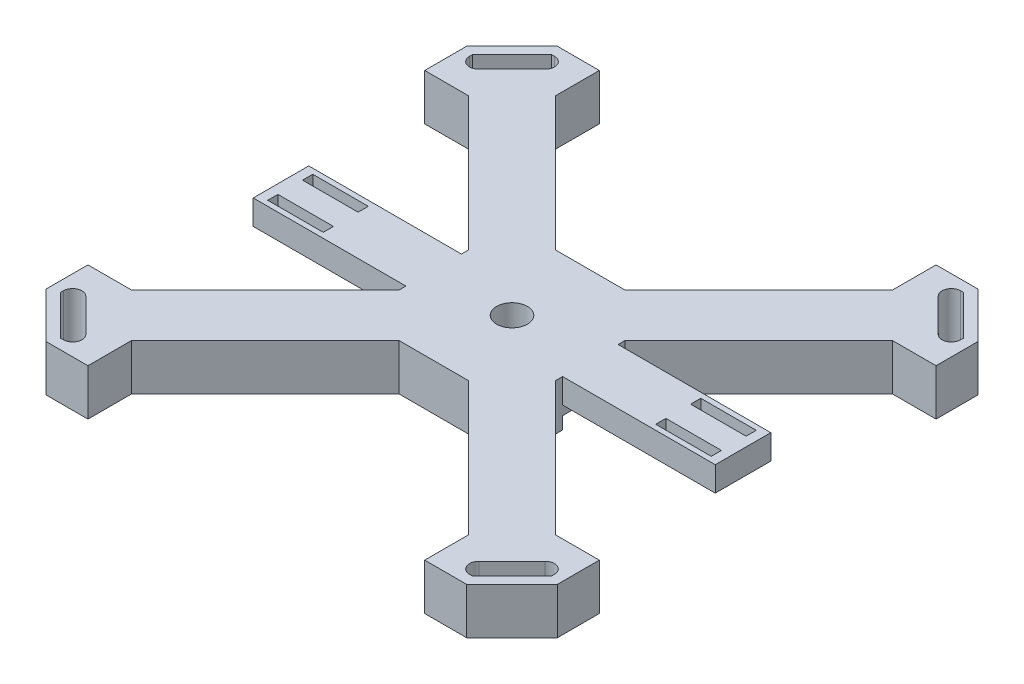
SolidWorks part; units mm, degrees
material "Strong and Flexible"
ref_plane "Front Plane" through (0, 0, 0) normal (0, 0, 1) x (1, 0, 0)
ref_plane "Top Plane" through (0, 0, 0) normal (0, 1, 0) x (1, 0, 0)
ref_plane "Right Plane" through (0, 0, 0) normal (1, 0, 0) x (0, 0, -1)
sketch "Sketch1" plane through (0, 0, 0) normal (0, 1, 0) x (1, 0, 0)
  line L0 (0, 0) -> (0, 56.4488) construction
  line L1 (0, 0) -> (-71.4488, 0) construction
  line L2 (-39.7988, 33.4083) -> (-33.4083, 39.7988)
  line L3 (-33.4083, -39.7988) -> (-29.2929, -39.7988)
  line L4 (-39.7988, -33.4083) -> (-39.7988, -29.2929)
  line L5 (-33.4083, 39.7988) -> (-29.2929, 39.7988)
  line L6 (39.7988, -33.4083) -> (39.7988, -29.2929)
  line L7 (-39.7988, -39.7988) -> (36.6035, 36.6035) construction
  line L8 (-36.6035, 36.6035) -> (39.7988, -39.7988) construction
  line L9 (33.4083, 39.7988) -> (39.7988, 33.4083)
  line L10 (39.7988, -33.4083) -> (33.4083, -39.7988)
  line L11 (-33.4083, -39.7988) -> (-39.7988, -33.4083)
  line L12 (-41.4488, 34.0917) -> (-34.0917, 41.4488)
  line L13 (34.0917, 41.4488) -> (27.2929, 41.4488)
  line L14 (34.0917, 41.4488) -> (41.4488, 34.0917)
  line L15 (41.4488, -27.2929) -> (41.4488, -34.0917)
  line L16 (41.4488, -34.0917) -> (34.0917, -41.4488)
  line L17 (-27.2929, -41.4488) -> (-34.0917, -41.4488)
  line L18 (-34.0917, -41.4488) -> (-41.4488, -34.0917)
  line L19 (-41.4488, 34.0917) -> (-41.4488, 27.2929)
  line L20 (-39.7988, 29.2929) -> (-29.2929, 39.7988)
  line L21 (5.6289, 12.7) -> (27.2929, 34.364)
  line L22 (29.2929, 39.7988) -> (39.7988, 29.2929)
  line L23 (27.2929, 34.364) -> (27.2929, 41.4488)
  line L24 (39.7988, -29.2929) -> (29.2929, -39.7988)
  line L25 (5.6289, -12.7) -> (27.2929, -34.364)
  line L26 (-29.2929, -39.7988) -> (-39.7988, -29.2929)
  line L27 (-34.364, -27.2929) -> (-41.4488, -27.2929)
  line L28 (-39.7988, 29.2929) -> (-39.7988, 33.4083)
  line L30 (29.2929, 39.7988) -> (33.4083, 39.7988)
  line L31 (39.7988, 29.2929) -> (39.7988, 33.4083)
  line L32 (41.4488, 34.0917) -> (41.4488, 27.2929)
  line L33 (12.7, 5.6289) -> (34.364, 27.2929)
  line L34 (27.2929, -41.4488) -> (34.0917, -41.4488)
  line L35 (29.2929, -39.7988) -> (33.4083, -39.7988)
  line L36 (-12.7, 5.6289) -> (-34.364, 27.2929)
  line L37 (-34.364, 27.2929) -> (-41.4488, 27.2929)
  line L38 (-5.6289, 12.7) -> (-27.2929, 34.364)
  line L39 (-27.2929, 34.364) -> (-27.2929, 41.4488)
  line L40 (-34.0917, 41.4488) -> (-27.2929, 41.4488)
  line L41 (34.364, 27.2929) -> (41.4488, 27.2929)
  line L42 (27.2929, -34.364) -> (27.2929, -41.4488)
  line L43 (12.7, -5.6289) -> (34.364, -27.2929)
  line L44 (0, 0) -> (0, -61.4488) construction
  line L46 (34.364, -27.2929) -> (41.4488, -27.2929)
  line L47 (-41.4488, -27.2929) -> (-41.4488, -34.0917)
  line L49 (-27.2929, -34.364) -> (-27.2929, -41.4488)
  line L50 (-5.6289, -12.7) -> (5.6289, -12.7)
  line L51 (-12.7, -5.6289) -> (-12.7, 5.6289)
  line L52 (-5.6289, 12.7) -> (5.6289, 12.7)
  line L53 (12.7, -5.6289) -> (12.7, 5.6289)
  line L54 (-12.7, -5.6289) -> (-34.364, -27.2929)
  line L55 (-5.6289, -12.7) -> (-27.2929, -34.364)
  circle A0 centre (0, 0) radius 2.5
  point P19 (0, 0)
  point P20 (0, 0)
  point P33 (0, 0)
  point P46 (0, 0)
  point P74 (0, 0)
  dimension "D10" = 5
  dimension "D11" = 5
  dimension "D15" = 1.65
  dimension "D16" = 1.65
  dimension "D17" = 5
  dimension "D1" = 5
  dimension "D2" = 79.5976
  dimension "D3" = 9.0376
  dimension "D5" = 1.65
  dimension "D6" = 4
  dimension "D7" = 2.91
  dimension "D8" = 5
  dimension "D12" = 5
  dimension "D13" = 25.4
  dimension "D14" = 25.4
  dimension "D19" = 2
  dimension "D30" = 5
  dimension "D31" = 5
  dimension "D9" = 5
  dimension "D4" = 4
extrude "Boss-Extrude1" add sketch "Sketch1" along normal blind 7.5
fillet "Fillet3" radius 1.5 8 edges at (29.2929, 3.75, 39.7988) (39.7988, 3.75, 29.2929) (-29.2929, 3.75, 39.7988) (-39.7988, 3.75, 29.2929) (-39.7988, 3.75, -29.2929) (-29.2929, 3.75, -39.7988) (39.7988, 3.75, -29.2929) (29.2929, 3.75, -39.7988)
sketch "Sketch2" plane through (0, 7.5, 0) normal (0, 1, 0) x (1, 0, 0)
  line L0 (-41.4488, -27.2929) -> (-41.4488, 27.2929) construction
  line L1 (41.4488, -27.2929) -> (41.4488, 27.2929) construction
  line L2 (12.7, -4.5) -> (37.4488, -4.5)
  line L3 (12.7, -5.6289) -> (12.7, 5.6289) construction
  line L4 (37.4488, -4.5) -> (37.4488, 4.5)
  line L5 (37.4488, 4.5) -> (12.7, 4.5)
  line L6 (-12.7, -4.5) -> (-37.4488, -4.5)
  line L7 (-12.7, 5.6289) -> (-12.7, -5.6289) construction
  line L8 (-37.4488, -4.5) -> (-37.4488, 4.5)
  line L9 (-37.4488, 4.5) -> (-12.7, 4.5)
  line L10 (31.4488, -23.3224) -> (31.4488, 21.664) construction
  line L11 (-31.4488, -18.7769) -> (-31.4488, 20.7153) construction
  line L12 (-31.1686, 0) -> (56.5686, 0) construction
  line L13 (12.7, 4.5) -> (12.7, -4.5)
  line L14 (35.9488, 3.651) -> (26.9488, 3.651)
  line L15 (35.9488, 3.651) -> (35.9488, 2)
  line L16 (35.9488, 2) -> (26.9488, 2)
  line L17 (26.9488, 3.651) -> (26.9488, 2)
  line L18 (35.9488, -3.651) -> (26.9488, -3.651)
  line L19 (35.9488, -3.651) -> (35.9488, -2)
  line L20 (35.9488, -2) -> (26.9488, -2)
  line L21 (26.9488, -3.651) -> (26.9488, -2)
  line L22 (-12.7, 4.5) -> (-12.7, -4.5)
  line L24 (-35.9488, 3.651) -> (-26.9488, 3.651)
  line L25 (-35.9488, 3.651) -> (-35.9488, 2)
  line L26 (-35.9488, 2) -> (-26.9488, 2)
  line L27 (-26.9488, 3.651) -> (-26.9488, 2)
  line L28 (-35.9488, -3.651) -> (-26.9488, -3.651)
  line L29 (-35.9488, -3.651) -> (-35.9488, -2)
  line L30 (-35.9488, -2) -> (-26.9488, -2)
  line L31 (-26.9488, -3.651) -> (-26.9488, -2)
  point P24 (-25.0744, 4.5)
  point P27 (12.7, 0)
  dimension "D1" = 10
  dimension "D2" = 10
  dimension "D3" = 6
  dimension "D4" = 6
  dimension "D5" = 4.5
  dimension "D6" = 4.5
  dimension "D7" = 4.5
  dimension "D8" = 4.5
  dimension "D9" = 9
  dimension "D10" = 1.651
  dimension "D11" = 4.5
  dimension "D12" = 2
  dimension "D13" = 2
  dimension "D14" = 4.5
sketch "Sketch3" plane through (0, 0, 0) normal (0, -1, 0) x (1, 0, 0)
  line L0 (-12.7, -4.5) -> (12.7, -4.5)
  line L1 (-12.7, -5.6289) -> (-12.7, 5.6289) construction
  line L2 (12.7, 5.6289) -> (12.7, -5.6289) construction
  line L3 (12.7, -4.5) -> (12.7, 4.5)
  line L4 (12.7, 4.5) -> (-12.7, 4.5)
  line L5 (-12.7, 4.5) -> (-12.7, -4.5)
  line L6 (-31.1686, 0) -> (56.5686, 0) construction
  dimension "D1" = 9
  dimension "D2" = 4.5
extrude "Cut-Extrude1" cut sketch "Sketch3" against normal blind 2
extrude "Boss-Extrude3" add sketch "Sketch2" against normal blind 3
sketch "Sketch4" plane through (0, 4.5, 0) normal (0, -1, 0) x (1, 0, 0)
  line L1 (37.4488, -4.5) -> (12.7, -4.5)
  line L2 (37.4488, -4.5) -> (37.4488, 4.5)
  line L3 (37.4488, 4.5) -> (12.7, 4.5)
  line L4 (12.7, -4.5) -> (12.7, 4.5)
  line L5 (-37.4488, -4.5) -> (-12.7, -4.5)
  line L6 (-37.4488, -4.5) -> (-37.4488, 4.5)
  line L7 (-37.4488, 4.5) -> (-12.7, 4.5)
  line L8 (-12.7, -4.5) -> (-12.7, 4.5)
extrude "Boss-Extrude4" add sketch "Sketch4" along normal blind 1
